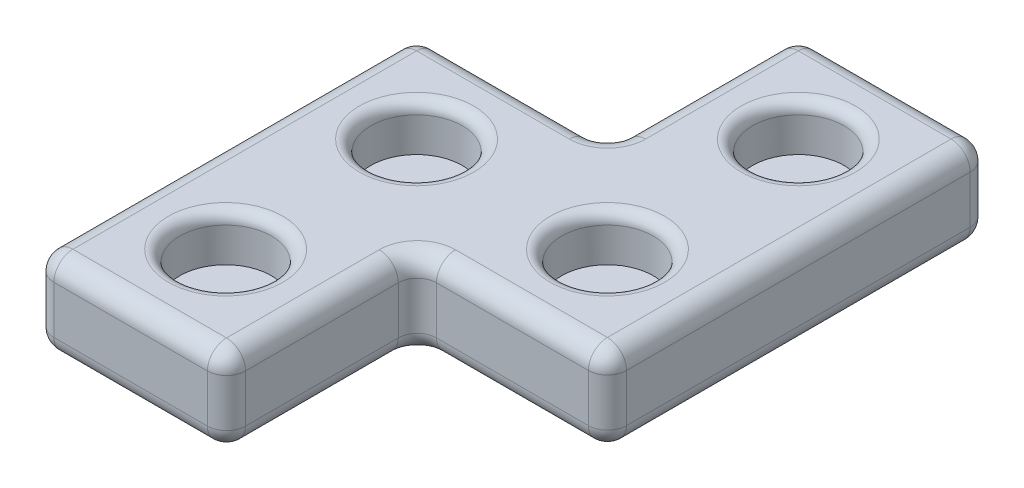
SolidWorks part; units mm, degrees
ref_plane "Front Plane" through (0, 0, 0) normal (0, 0, 1) x (1, 0, 0)
ref_plane "Top Plane" through (0, 0, 0) normal (0, 1, 0) x (1, 0, 0)
ref_plane "Right Plane" through (0, 0, 0) normal (1, 0, 0) x (0, 0, -1)
sketch "Sketch1" plane through (0, 0, 0) normal (0, 1, 0) x (1, 0, 0)
  line L0 (-7.6659, 2.6651) -> (-7.6659, 12.8251)
  line L1 (-6.3959, 14.0951) -> (3.7641, 14.0951)
  line L2 (5.0341, 12.8251) -> (5.0341, -10.0349)
  line L3 (3.7641, -11.3049) -> (-6.3409, -11.3049)
  line L4 (-7.6109, -12.5749) -> (-7.6109, -22.7349)
  line L5 (-8.8809, -24.0049) -> (-19.0959, -24.0049)
  line L6 (-20.3659, -22.7349) -> (-20.3659, 0.1251)
  line L7 (-19.0959, 1.3951) -> (-8.9359, 1.3951)
  arc A0 (-7.6659, 2.6651) -> (-8.9359, 1.3951) centre (-8.9359, 2.6651) cw
  arc A1 (-6.3409, -11.3049) -> (-7.6109, -12.5749) centre (-6.3409, -12.5749) ccw
  arc A2 (-7.6109, -22.7349) -> (-8.8809, -24.0049) centre (-8.8809, -22.7349) cw
  arc A3 (-19.0959, -24.0049) -> (-20.3659, -22.7349) centre (-19.0959, -22.7349) cw
  arc A4 (-20.3659, 0.1251) -> (-19.0959, 1.3951) centre (-19.0959, 0.1251) cw
  arc A5 (5.0341, -10.0349) -> (3.7641, -11.3049) centre (3.7641, -10.0349) cw
  arc A6 (-7.6659, 12.8251) -> (-6.3959, 14.0951) centre (-6.3959, 12.8251) cw
  arc A7 (3.7641, 14.0951) -> (5.0341, 12.8251) centre (3.7641, 12.8251) cw
  point P10 (-7.6659, 1.3951)
  point P13 (-7.6109, -11.3049)
  point P18 (-20.3659, -24.0049)
  point P21 (-20.3659, 1.3951)
  point P24 (5.0341, -11.3049)
  point P27 (-7.6659, 14.0951)
  point P30 (5.0341, 14.0951)
  dimension "D7" = 1.27
  dimension "D1" = 12.7
  dimension "D2" = 25.4
  dimension "D3" = 12.7
  dimension "D4" = 25.4
  dimension "D5" = 12.645
  dimension "D6" = 12.7
extrude "Boss-Extrude1" add sketch "Sketch1" along normal blind 5.715
sketch "Sketch2" plane through (0, 5.715, 0) normal (0, 1, 0) x (1, 0, 0)
  line L0 (5.0341, -10.0349) -> (5.0341, 12.8251) construction
  line L1 (-19.0959, -24.0049) -> (-8.8809, -24.0049) construction
  circle A0 centre (-1.3159, 7.7451) radius 3.048
  circle A1 centre (-14.0159, -4.9549) radius 3.048
  circle A2 centre (-14.0159, -17.6549) radius 3.048
  circle A3 centre (-1.3159, -4.9549) radius 3.048
  point P8 (0, 0)
  point P9 (0, 0)
  point P12 (0, 0)
  point P13 (0, 0)
  point P14 (1.5389, 5.8276)
  dimension "D1" = 6.35
  dimension "D2" = 12.7
  dimension "D3" = 12.7
  dimension "D4" = 12.7
  dimension "D5" = 6.35
extrude "Cut-Extrude1" cut sketch "Sketch2" against normal blind 3.048
fillet "Fillet1" radius 1.27 16 edges at (-1.2884, 5.715, 11.3049) (-7.6109, 5.715, 17.6549) (-13.9884, 5.715, 24.0049) (-20.3659, 5.715, 11.3049) (-14.0159, 5.715, -1.3951) (-7.6659, 5.715, -7.7451) (-1.3159, 5.715, -14.0951) (5.0341, 5.715, -1.3951) (4.6621, 5.715, 10.9329) (-7.2389, 5.715, 11.6769) (-7.9829, 5.715, 23.6329) (-19.9939, 5.715, 23.6329) (-19.9939, 5.715, -1.0231) (-8.0379, 5.715, -1.7671) (-7.2939, 5.715, -13.7231) (4.6621, 5.715, -13.7231)
fillet "Fillet2" radius 1.27 16 edges at (-1.3159, 0, -14.0951) (-7.6659, 0, -7.7451) (-14.0159, 0, -1.3951) (-20.3659, 0, 11.3049) (-13.9884, 0, 24.0049) (-7.6109, 0, 17.6549) (-1.2884, 0, 11.3049) (5.0341, 0, -1.3951) (4.6621, 0, 10.9329) (-7.2389, 0, 11.6769) (-7.9829, 0, 23.6329) (-19.9939, 0, 23.6329) (-19.9939, 0, -1.0231) (-8.0379, 0, -1.7671) (-7.2939, 0, -13.7231) (4.6621, 0, -13.7231)
fillet "Fillet3" radius 0.762 4 edges at (-14.0159, 5.715, 20.7029) (-14.0159, 5.715, 8.0029) (-1.3159, 5.715, 8.0029) (-1.3159, 5.715, -4.6971)
